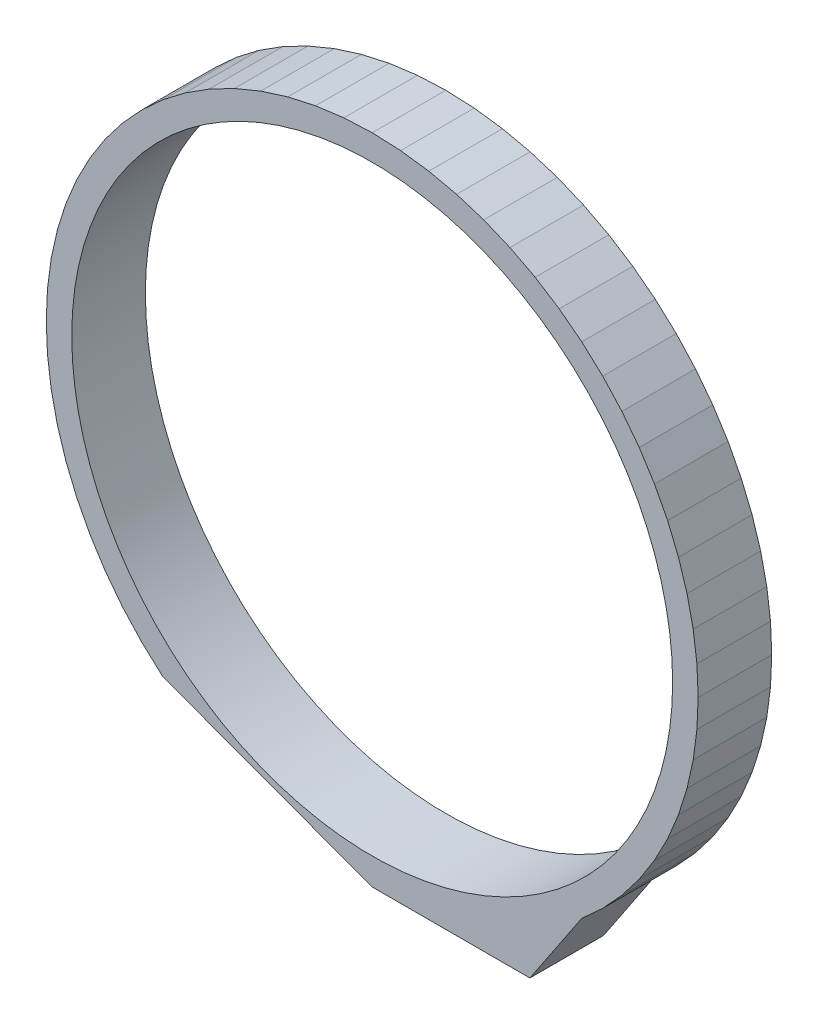
SolidWorks part; units mm, degrees
ref_plane "前视基准面" through (0, 0, 0) normal (0, 0, 1) x (1, 0, 0)
ref_plane "上视基准面" through (0, 0, 0) normal (0, 1, 0) x (1, 0, 0)
ref_plane "右视基准面" through (0, 0, 0) normal (1, 0, 0) x (0, 0, -1)
other "Configuration Table"
sketch "草图1" plane through (0, 0, 0) normal (0, 0, 1) x (1, 0, 0)
  line L0 (39.8528, -47.4948) -> (43.8406, -43.8406)
  line L1 (43.8406, -43.8406) -> (47.4948, -39.8528)
  line L2 (47.4948, -39.8528) -> (50.7874, -35.5617)
  line L3 (50.7874, -35.5617) -> (53.6936, -31)
  line L4 (53.6936, -31) -> (56.1911, -26.2023)
  line L5 (56.1911, -26.2023) -> (58.2609, -21.2052)
  line L6 (58.2609, -21.2052) -> (59.8874, -16.0468)
  line L7 (59.8874, -16.0468) -> (61.0581, -10.7662)
  line L8 (61.0581, -10.7662) -> (61.7641, -5.4037)
  line L9 (61.7641, -5.4037) -> (62, 0)
  line L10 (62, 0) -> (61.7641, 5.4037)
  line L11 (61.7641, 5.4037) -> (61.0581, 10.7662)
  line L12 (61.0581, 10.7662) -> (59.8874, 16.0468)
  line L13 (59.8874, 16.0468) -> (58.2609, 21.2052)
  line L14 (58.2609, 21.2052) -> (56.1911, 26.2023)
  line L15 (56.1911, 26.2023) -> (53.6936, 31)
  line L16 (53.6936, 31) -> (50.7874, 35.5617)
  line L17 (50.7874, 35.5617) -> (47.4948, 39.8528)
  line L18 (47.4948, 39.8528) -> (43.8406, 43.8406)
  line L19 (43.8406, 43.8406) -> (39.8528, 47.4948)
  line L20 (39.8528, 47.4948) -> (35.5617, 50.7874)
  line L21 (35.5617, 50.7874) -> (31, 53.6936)
  line L22 (31, 53.6936) -> (26.2023, 56.1911)
  line L23 (26.2023, 56.1911) -> (21.2052, 58.2609)
  line L24 (21.2052, 58.2609) -> (16.0468, 59.8874)
  line L25 (16.0468, 59.8874) -> (10.7662, 61.0581)
  line L26 (10.7662, 61.0581) -> (5.4037, 61.7641)
  line L27 (5.4037, 61.7641) -> (0, 62)
  line L28 (0, 62) -> (-5.4037, 61.7641)
  line L29 (-5.4037, 61.7641) -> (-10.7662, 61.0581)
  line L30 (-10.7662, 61.0581) -> (-16.0468, 59.8874)
  line L31 (-16.0468, 59.8874) -> (-21.2052, 58.2609)
  line L32 (-21.2052, 58.2609) -> (-26.2023, 56.1911)
  line L33 (-26.2023, 56.1911) -> (-31, 53.6936)
  line L34 (-31, 53.6936) -> (-35.5617, 50.7874)
  line L35 (-35.5617, 50.7874) -> (-39.8528, 47.4948)
  line L36 (-39.8528, 47.4948) -> (-43.8406, 43.8406)
  line L37 (-43.8406, 43.8406) -> (-47.4948, 39.8528)
  line L38 (-47.4948, 39.8528) -> (-50.7874, 35.5617)
  line L39 (-50.7874, 35.5617) -> (-53.6936, 31)
  line L40 (-53.6936, 31) -> (-56.1911, 26.2023)
  line L41 (-56.1911, 26.2023) -> (-58.2609, 21.2052)
  line L42 (-58.2609, 21.2052) -> (-59.8874, 16.0468)
  line L43 (-59.8874, 16.0468) -> (-61.0581, 10.7662)
  line L44 (-61.0581, 10.7662) -> (-61.7641, 5.4037)
  line L45 (-61.7641, 5.4037) -> (-62, 0)
  line L46 (-62, 0) -> (-61.7641, -5.4037)
  line L47 (-61.7641, -5.4037) -> (-61.0581, -10.7662)
  line L48 (-61.0581, -10.7662) -> (-59.8874, -16.0468)
  line L49 (-59.8874, -16.0468) -> (-58.2609, -21.2052)
  line L50 (-58.2609, -21.2052) -> (-56.1911, -26.2023)
  line L51 (-56.1911, -26.2023) -> (-53.6936, -31)
  line L52 (-53.6936, -31) -> (-50.7874, -35.5617)
  line L53 (-50.7874, -35.5617) -> (-47.4948, -39.8528)
  line L54 (-47.4948, -39.8528) -> (-43.8406, -43.8406)
  line L55 (-43.8406, -43.8406) -> (-39.8528, -47.4948)
  line L56 (-39.8528, -47.4948) -> (-0.0065, -62.24)
  line L57 (-0.0065, -62.24) -> (29.9935, -62.24)
  line L58 (29.9935, -62.24) -> (39.8528, -47.4948)
  dimension "x0" = 39.8528
  dimension "x1" = 43.8406
  dimension "x2" = 47.4948
  dimension "x3" = 50.7874
  dimension "x4" = 53.6936
  dimension "x5" = 56.1911
  dimension "x6" = 58.2609
  dimension "x7" = 59.8874
  dimension "x8" = 61.0581
  dimension "x9" = 61.7641
  dimension "x10" = 62
  dimension "x11" = 61.7641
  dimension "x12" = 61.0581
  dimension "x13" = 59.8874
  dimension "x14" = 58.2609
  dimension "x15" = 56.1911
  dimension "x16" = 53.6936
  dimension "x17" = 50.7874
  dimension "x18" = 47.4948
  dimension "x19" = 43.8406
  dimension "x20" = 39.8528
  dimension "x21" = 35.5617
  dimension "x22" = 31
  dimension "x23" = 26.2023
  dimension "x24" = 21.2052
  dimension "x25" = 16.0468
  dimension "x26" = 10.7662
  dimension "x27" = 5.4037
  dimension "x29" = 5.4037
  dimension "x30" = 10.7662
  dimension "x31" = 16.0468
  dimension "x32" = 21.2052
  dimension "x33" = 26.2023
  dimension "x34" = 31
  dimension "x35" = 35.5617
  dimension "x36" = 39.8528
  dimension "x37" = 43.8406
  dimension "x38" = 47.4948
  dimension "x39" = 50.7874
  dimension "x40" = 53.6936
  dimension "x41" = 56.1911
  dimension "x42" = 58.2609
  dimension "x43" = 59.8874
  dimension "x44" = 61.0581
  dimension "x45" = 61.7641
  dimension "x46" = 62
  dimension "x47" = 61.7641
  dimension "x48" = 61.0581
  dimension "x49" = 59.8874
  dimension "x50" = 58.2609
  dimension "x51" = 56.1911
  dimension "x52" = 53.6936
  dimension "x53" = 50.7874
  dimension "x54" = 47.4948
  dimension "x55" = 43.8406
  dimension "x56" = 39.8528
  dimension "x57" = 0.0065
  dimension "x58" = 29.9935
  dimension "y0" = 47.4948
  dimension "y1" = 43.8406
  dimension "y2" = 39.8528
  dimension "y3" = 35.5617
  dimension "y4" = 31
  dimension "y5" = 26.2023
  dimension "y6" = 21.2052
  dimension "y7" = 16.0468
  dimension "y8" = 10.7662
  dimension "y9" = 5.4037
  dimension "y11" = 5.4037
  dimension "y12" = 10.7662
  dimension "y13" = 16.0468
  dimension "y14" = 21.2052
  dimension "y15" = 26.2023
  dimension "y16" = 31
  dimension "y17" = 35.5617
  dimension "y18" = 39.8528
  dimension "y19" = 43.8406
  dimension "y20" = 47.4948
  dimension "y21" = 50.7874
  dimension "y22" = 53.6936
  dimension "y23" = 56.1911
  dimension "y24" = 58.2609
  dimension "y25" = 59.8874
  dimension "y26" = 61.0581
  dimension "y27" = 61.7641
  dimension "y28" = 62
  dimension "y29" = 61.7641
  dimension "y30" = 61.0581
  dimension "y31" = 59.8874
  dimension "y32" = 58.2609
  dimension "y33" = 56.1911
  dimension "y34" = 53.6936
  dimension "y35" = 50.7874
  dimension "y36" = 47.4948
  dimension "y37" = 43.8406
  dimension "y38" = 39.8528
  dimension "y39" = 35.5617
  dimension "y40" = 31
  dimension "y41" = 26.2023
  dimension "y42" = 21.2052
  dimension "y43" = 16.0468
  dimension "y44" = 10.7662
  dimension "y45" = 5.4037
  dimension "y47" = 5.4037
  dimension "y48" = 10.7662
  dimension "y49" = 16.0468
  dimension "y50" = 21.2052
  dimension "y51" = 26.2023
  dimension "y52" = 31
  dimension "y53" = 35.5617
  dimension "y54" = 39.8528
  dimension "y55" = 43.8406
  dimension "y56" = 47.4948
  dimension "y57" = 62.24
extrude "Clamp_and_lower_foot" add sketch "草图1" along normal blind 14
sketch "草图2" plane through (0, 0, 14) normal (0, 0, 1) x (1, 0, 0)
  circle A0 centre (0, 0) radius 57.15
  dimension "diameter" = 114.3
extrude "Canister_seat" cut sketch "草图2" against normal through all
